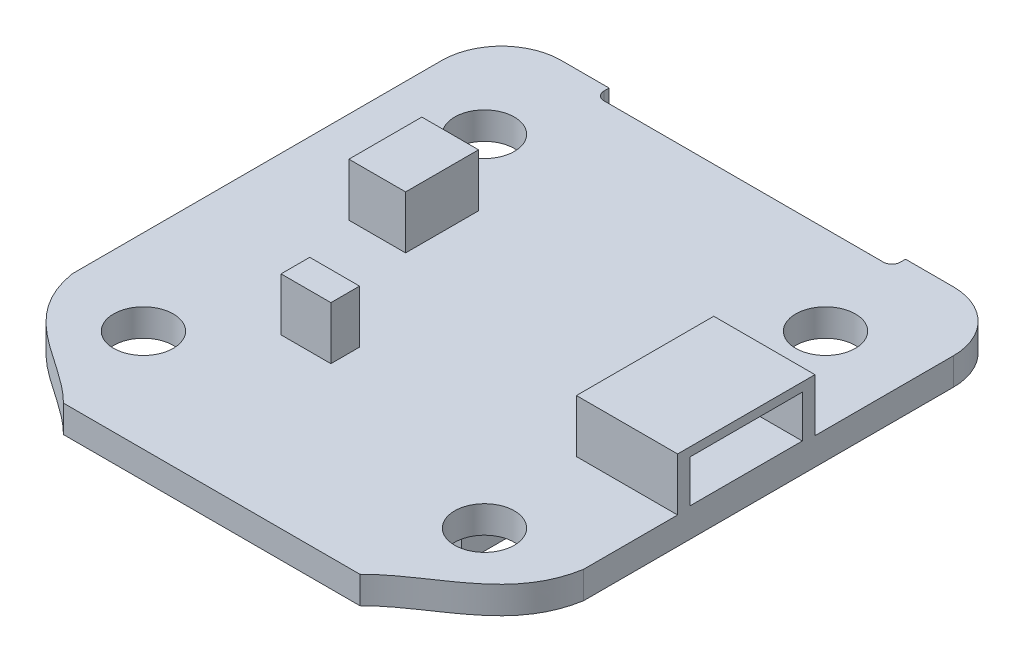
SolidWorks part; units mm, degrees
ref_plane "Front Plane" through (0, 0, 0) normal (0, 0, 1) x (1, 0, 0)
ref_plane "Top Plane" through (0, 0, 0) normal (0, 1, 0) x (1, 0, 0)
ref_plane "Right Plane" through (0, 0, 0) normal (1, 0, 0) x (0, 0, -1)
sketch "Sketch1" plane through (0, 0, 0) normal (0, 1, 0) x (1, 0, 0)
  line L0 (0, 0) -> (0, -16) construction
  line L1 (-8.6928, -16) -> (8.6928, -16)
  line L2 (-15, -9.1838) -> (-15, 12.5)
  line L3 (-11.5, 16) -> (-8.6928, 16)
  line L4 (15, -9.1838) -> (15, 12.5)
  line L5 (-15, -16) -> (15, 16) construction
  line L6 (-15, 16) -> (15, -16) construction
  line L7 (10, -10) -> (-10, -10) construction
  line L8 (10, -10) -> (10, 10) construction
  line L9 (10, 10) -> (-10, 10) construction
  line L10 (-10, -10) -> (-10, 10) construction
  line L11 (10, -10) -> (-10, 10) construction
  line L12 (10, 10) -> (-10, -10) construction
  line L13 (8.6928, 16) -> (11.5, 16)
  line L14 (8.1928, 15.2007) -> (-8.1928, 15.2007)
  line L15 (8.6928, 15.7007) -> (8.6928, 16)
  line L17 (-8.6928, 15.7007) -> (-8.6928, 16)
  circle A0 centre (-10, 10) radius 1.75
  circle A1 centre (10, 10) radius 1.75
  circle A2 centre (10, -10) radius 1.75
  circle A3 centre (-10, -10) radius 1.75
  arc A4 (11.5, 16) -> (15, 12.5) centre (11.5, 12.5) cw
  arc A5 (-15, 12.5) -> (-11.5, 16) centre (-11.5, 12.5) cw
  arc A6 (8.1928, 15.2007) -> (8.6928, 15.7007) centre (8.1928, 15.7007) ccw
  arc A7 (-8.1928, 15.2007) -> (-8.6928, 15.7007) centre (-8.1928, 15.7007) cw
  spline S0 degree 3 poles (-15, -9.1838) (-14.3663, -12.9511) (-10.8673, -13.8016) (-8.6928, -16) knots 0 0 0 0 0.91531 0.91531 0.91531 0.91531
  spline S1 degree 3 poles (15, -9.1838) (14.3663, -12.9511) (10.8673, -13.8016) (8.6928, -16) knots 0 0 0 0 0.91531 0.91531 0.91531 0.91531
  point P0 (0, 0)
  point P6 (0, 0)
  point P26 (0, 16)
  dimension "D5" = 3.5
  dimension "D6" = 0.5
  dimension "D1" = 30
  dimension "D2" = 32
  dimension "D3" = 20
  dimension "D4" = 20
extrude "Boss-Extrude1" add sketch "Sketch1" along normal blind 1.6
sketch "Sketch2" plane through (0, 1.6, 0) normal (0, 1, 0) x (1, 0, 0)
  line L0 (15, -9.1838) -> (15, 12.5) construction
  line L1 (15, 4.379) -> (9.066, 4.379)
  line L2 (15, 4.379) -> (15, -3.6748)
  line L3 (15, -3.6748) -> (9.066, -3.6748)
  line L4 (9.066, 4.379) -> (9.066, -3.6748)
  line L6 (-9.6084, 5.9349) -> (-6.2843, 5.9349)
  line L7 (-9.6084, 5.9349) -> (-9.6084, 1.6581)
  line L8 (-9.6084, 1.6581) -> (-6.2843, 1.6581)
  line L9 (-6.2843, 5.9349) -> (-6.2843, 1.6581)
  line L10 (-5.7729, -4.4757) -> (-2.8507, -4.4757)
  line L11 (-5.7729, -4.4757) -> (-5.7729, -6.156)
  line L12 (-5.7729, -6.156) -> (-2.8507, -6.156)
  line L13 (-2.8507, -4.4757) -> (-2.8507, -6.156)
extrude "Boss-Extrude2" add sketch "Sketch2" along normal blind 3.1
sketch "Sketch3" plane through (0, 0, 0) normal (0, -1, 0) x (1, 0, 0)
  line L1 (-11.9707, -0.4181) -> (-8.2299, -0.4181)
  line L2 (-11.9707, -0.4181) -> (-11.9707, -5.3912)
  line L3 (-11.9707, -5.3912) -> (-8.2299, -5.3912)
  line L4 (-8.2299, -0.4181) -> (-8.2299, -5.3912)
  line L5 (-4.6651, 7.8118) -> (6.4695, 7.8118)
  line L6 (-4.6651, 7.8118) -> (-4.6651, -6.5795)
  line L7 (-4.6651, -6.5795) -> (6.4695, -6.5795)
  line L8 (6.4695, 7.8118) -> (6.4695, -6.5795)
extrude "Boss-Extrude3" add sketch "Sketch3" along normal blind 3.1
sketch "Sketch4" plane through (15, 0, 0) normal (1, 0, 0) x (0, 0, -1)
  line L1 (-2.9587, 4.1838) -> (3.6388, 4.1838)
  line L2 (-2.9587, 4.1838) -> (-2.9587, 1.7012)
  line L3 (-2.9587, 1.7012) -> (3.6388, 1.7012)
  line L4 (3.6388, 4.1838) -> (3.6388, 1.7012)
extrude "Cut-Extrude1" cut sketch "Sketch4" against normal blind 5.1
